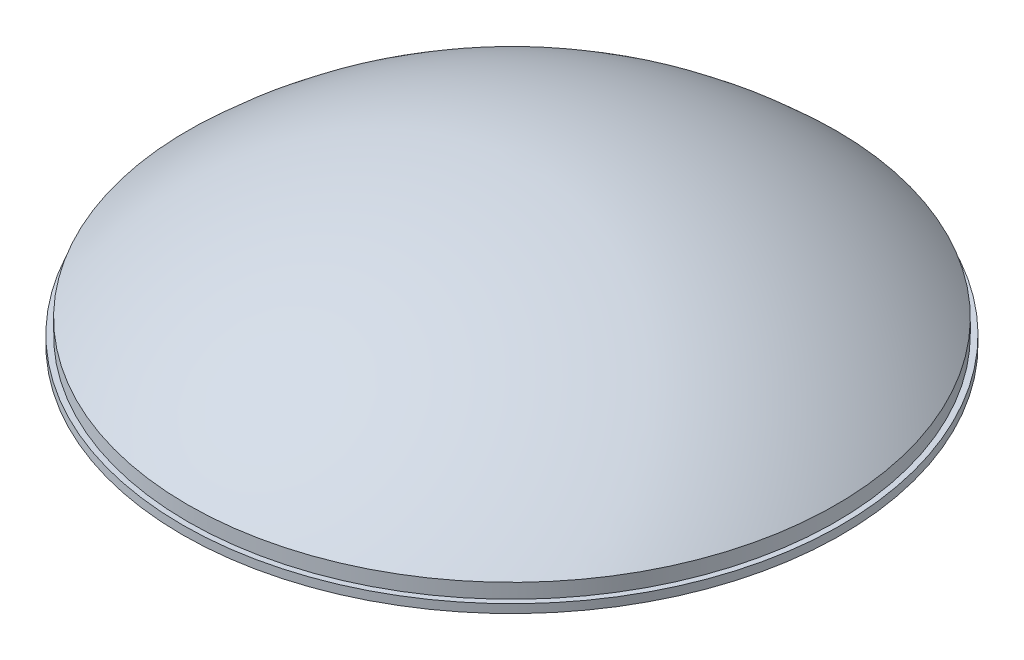
SolidWorks part; units mm, degrees
material "UVT Light Guide"
ref_plane "Front" through (0, 0, 0) normal (0, 0, 1) x (1, 0, 0)
ref_plane "Top" through (0, 0, 0) normal (0, 1, 0) x (1, 0, 0)
ref_plane "Right" through (0, 0, 0) normal (1, 0, 0) x (0, 0, -1)
sketch "Sketch1" plane through (0, 0, 0) normal (1, 0, 0) x (0, 0, -1)
  line L0 (0, 347) -> (0, 332) construction
  line L1 (249.6558, 241) -> (246.5, 241) construction
  line L2 (246.5, 241) -> (246.5, 229) construction
  line L3 (246.5, 229) -> (240.3809, 229) construction
  line L4 (0, 332) -> (0, 0) construction
  line L5 (0, 0) -> (54.2828, 342.7279) construction
  line L6 (26.55, 278) -> (44.0309, 278) construction
  line L7 (26.55, 258) -> (40.8632, 258) construction
  line L8 (26.25, 284) -> (26.25, 235.5) construction
  line L9 (23.25, 232.5) -> (0, 232.5) construction
  line L10 (26.55, 278) -> (26.55, 258) construction
  line L11 (22.2, 232.5) -> (22.2, 210.5) construction
  line L12 (21.2, 209.5) -> (0, 209.5) construction
  line L13 (49.2591, 319) -> (50.7013, 328.1057) construction
  line L14 (49.2591, 319) -> (39.2252, 310.1228) construction
  line L15 (29.1813, 290.9057) -> (36.1857, 297.6697) construction
  line L16 (27, 278) -> (27, 279) construction
  line L17 (27, 279) -> (42, 279) construction
  line L18 (42, 279) -> (42, 278) construction
  line L19 (26.4, 284) -> (43.7156, 284) construction
  line L20 (43.7156, 284) -> (48.9147, 316.8261) construction
  line L21 (48.4509, 317.3504) -> (40.8872, 310.6585) construction
  line L22 (40.5498, 309.9096) -> (40.5498, 304.1375) construction
  line L23 (29.2855, 290.7978) -> (36.2899, 297.5618) construction
  line L24 (36.2899, 297.5618) -> (38.7788, 299.9654) construction
  line L25 (48.4509, 317.3504) -> (48.9147, 316.8261) construction
  line L26 (30, 284) -> (30, 279) construction
  line L27 (40.7818, 311.5) -> (41.2457, 310.9757) construction
  line L28 (40, 284) -> (40, 279) construction
  line L29 (49.2591, 319) -> (49.7229, 318.4757) construction
  line L30 (49.7229, 318.4757) -> (48.4509, 317.3504) construction
  arc A0 (0, 347) -> (249.6558, 241) centre (0, 0) cw construction
  arc A1 (0, 332) -> (240.3809, 229) centre (0, 0) cw construction
  arc A2 (0, 330) -> (36.419, 314.7024) centre (0, 279) cw construction
  arc A3 (26.25, 284) -> (29.1813, 290.9057) centre (35.85, 284) cw construction
  arc A4 (23.25, 232.5) -> (26.25, 235.5) centre (23.25, 235.5) ccw construction
  arc A5 (36.1857, 297.6697) -> (36.419, 314.7024) centre (27.8498, 306.3018) ccw construction
  arc A6 (21.2, 209.5) -> (22.2, 210.5) centre (21.2, 210.5) ccw construction
  arc A7 (26.4, 284) -> (29.2855, 290.7978) centre (35.85, 284) cw construction
  arc A8 (40.5498, 309.9096) -> (40.8872, 310.6585) centre (41.5498, 309.9096) cw construction
  arc A9 (36.2899, 297.5618) -> (36.5261, 314.8074) centre (27.8498, 306.3018) ccw construction
  arc A10 (38.7788, 299.9654) -> (40.5498, 304.1375) centre (34.7498, 304.1375) ccw construction
  point P21 (0, 279)
  point P34 (22.2, 209.5)
  dimension "D1" = 347
  dimension "D2" = 332
  dimension "D16" = 51
  dimension "D17" = 9.6
  dimension "D19" = 140.5
  dimension "D20" = 12
  dimension "D21" = 51.5
  dimension "D23" = 3
  dimension "D24" = 1
  dimension "D31" = 1
  dimension "D32" = 5.8
  dimension "D3" = 241
  dimension "D4" = 229
  dimension "D5" = 246.5
  dimension "D6" = 9
  dimension "D7" = 278
  dimension "D8" = 20
  dimension "D9" = 26.25
  dimension "D10" = 0.3
  dimension "D11" = 232.5
  dimension "D12" = 23
  dimension "D13" = 22.2
  dimension "D14" = 1.25
  dimension "D15" = 97.5
  dimension "D18" = 44
  dimension "D22" = 13
  dimension "D25" = 15
  dimension "D26" = 1
  dimension "D27" = 27
  dimension "D28" = 0.7
  dimension "D29" = 0.7
  dimension "D33" = 30
  dimension "D34" = 5
  dimension "D35" = 10
  dimension "D36" = 0.7
  dimension "D37" = 7.5
  dimension "D30" = 0.15
sketch "Sketch2" plane through (0, 0, 0) normal (1, 0, 0) x (0, 0, -1)
  line L0 (246.5, 236.9583) -> (242.5, 236.9583) construction
  line L1 (242.5, 236.9583) -> (242.5, 241.2561)
  line L2 (246.5, 236.9583) -> (246.5, 230.9583) construction
  line L3 (0, 347) -> (0, 332) construction
  line L4 (244.5, 228.547) -> (-244.5, 228.547) construction
  line L5 (246.5, 244.2268) -> (246.5, 236.9583) construction
  line L6 (246.5, 241) -> (246.5, 229) construction
  line L7 (0, 347) -> (0, 332)
  line L8 (244.5, 228.547) -> (244.5, 230.96) construction
  line L9 (244.5, 229.7535) -> (240.1118, 229.7535) construction
  line L10 (242.5, 236.9583) -> (232.5398, 236.9583) construction
  line L11 (242.5, 241.2561) -> (238.5, 241.2561)
  line L12 (246.5, 230.9583) -> (238.5, 230.9583) construction
  line L13 (238.5, 241.2561) -> (238.5, 252.0451)
  line L14 (242.5, 236.9583) -> (242.5, 234.9561)
  line L15 (242.5, 234.9561) -> (234.5626, 234.9561)
  arc A1 (240.3809, 229) -> (0, 332) centre (0, 0) ccw construction
  arc A2 (246.5, 244.2268) -> (238.5, 252.0451) centre (0, 0) ccw construction
  arc A3 (238.5, 252.0451) -> (0, 347) centre (0, 0) ccw
  arc A4 (234.5626, 234.9561) -> (0, 332) centre (0, 0) ccw
  dimension "D1" = 4
  dimension "D2" = 8
  dimension "D3" = 6
  dimension "D4" = 2.4113
  dimension "D5" = 4.3882
  dimension "D6" = 4
  dimension "D7" = 2.0022
  dimension "D8" = 6.3
revolve "Revolve1" add sketch "Sketch2" angle 360 about L7
